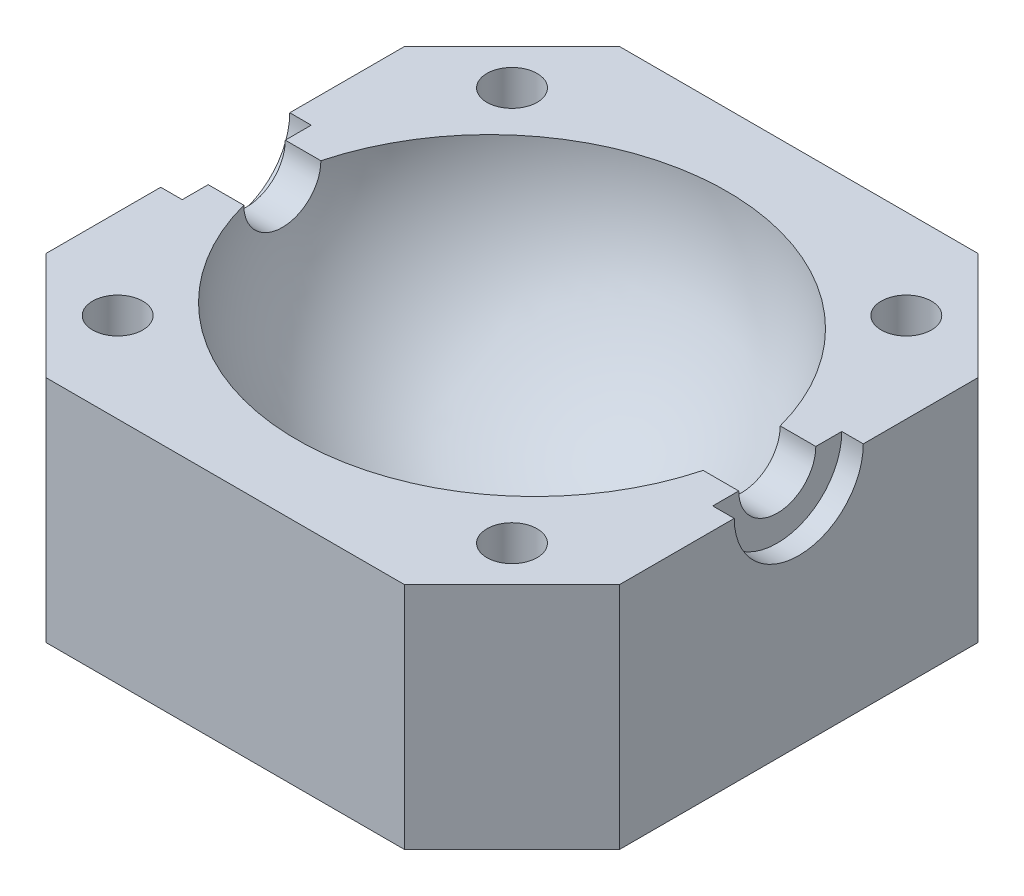
SolidWorks part; units mm, degrees
ref_plane "Front Plane" through (0, 0, 0) normal (0, 0, 1) x (1, 0, 0)
ref_plane "Top Plane" through (0, 0, 0) normal (0, 1, 0) x (1, 0, 0)
ref_plane "Right Plane" through (0, 0, 0) normal (1, 0, 0) x (0, 0, -1)
sketch "Sketch1" plane through (0, 0, 0) normal (0, 1, 0) x (1, 0, 0)
  line L1 (-40, 40) -> (40, 40)
  line L2 (-40, 40) -> (-40, -40)
  line L3 (-40, -40) -> (40, -40)
  line L4 (40, 40) -> (40, -40)
  line L5 (-40, 40) -> (40, -40) construction
  line L6 (-40, -40) -> (40, 40) construction
  point P0 (0, 0)
  dimension "D1" = 80
  dimension "D2" = 80
extrude "Boss-Extrude1" add sketch "Sketch1" along normal blind 32
sketch "Sketch2" plane through (0, 32, 0) normal (0, 1, 0) x (1, 0, 0)
  line L2 (0, 0) -> (0, -30) construction
  line L3 (-33, 0) -> (0, 0) construction
  line L4 (0, 0) -> (33, 0) construction
  line L5 (-33, 0) -> (33, 0)
  arc A1 (-33, 0) -> (33, 0) centre (0, 3.15) ccw
  dimension "D1" = 33
  dimension "D2" = 30
revolve "Cut-Revolve1" cut sketch "Sketch2" angle 360 about L5
sketch "Sketch3" plane through (-40, 0, 0) normal (-1, 0, 0) x (0, 0, 1)
  line L0 (-40, 32) -> (40, 32) construction
  line L1 (0, 32) -> (0, 0) construction
  circle A0 centre (0, 32) radius 5.375
  dimension "D1" = 10.75
extrude "Cut-Extrude1" cut sketch "Sketch3" against normal through all
chamfer "Chamfer1" distance 15 angle 45 4 edges at (40, 16, -40) (-40, 16, -40) (40, 16, 40) (-40, 16, 40)
sketch "Sketch4" plane through (0, 32, 0) normal (0, 1, 0) x (1, 0, 0)
  line L1 (27.5, -27.5) -> (-27.5, -27.5) construction
  line L2 (27.5, -27.5) -> (27.5, 27.5) construction
  line L3 (27.5, 27.5) -> (-27.5, 27.5) construction
  line L4 (-27.5, -27.5) -> (-27.5, 27.5) construction
  line L5 (27.5, -27.5) -> (-27.5, 27.5) construction
  line L6 (27.5, 27.5) -> (-27.5, -27.5) construction
  circle A0 centre (-27.5, 27.5) radius 3.5
  circle A1 centre (27.5, 27.5) radius 3.5
  circle A2 centre (27.5, -27.5) radius 3.5
  circle A3 centre (-27.5, -27.5) radius 3.5
  point P2 (0, 0)
  dimension "D2" = 7
  dimension "D1" = 55
extrude "Cut-Extrude2" cut sketch "Sketch4" against normal blind 7.5
ref_plane "Plane1" through (-37, 0, 0) normal (-1, 0, 0) x (0, 0, 1)
sketch "Sketch5" plane through (-37, 0, 0) normal (-1, 0, 0) x (0, 0, 1)
  circle A0 centre (0, 32) radius 9
  dimension "D1" = 18
extrude "Cut-Extrude3" cut sketch "Sketch5" along normal through all contours A0
mirror "Mirror1" about plane through (0, 0, 0) normal (1, 0, 0) of "Cut-Extrude3"
